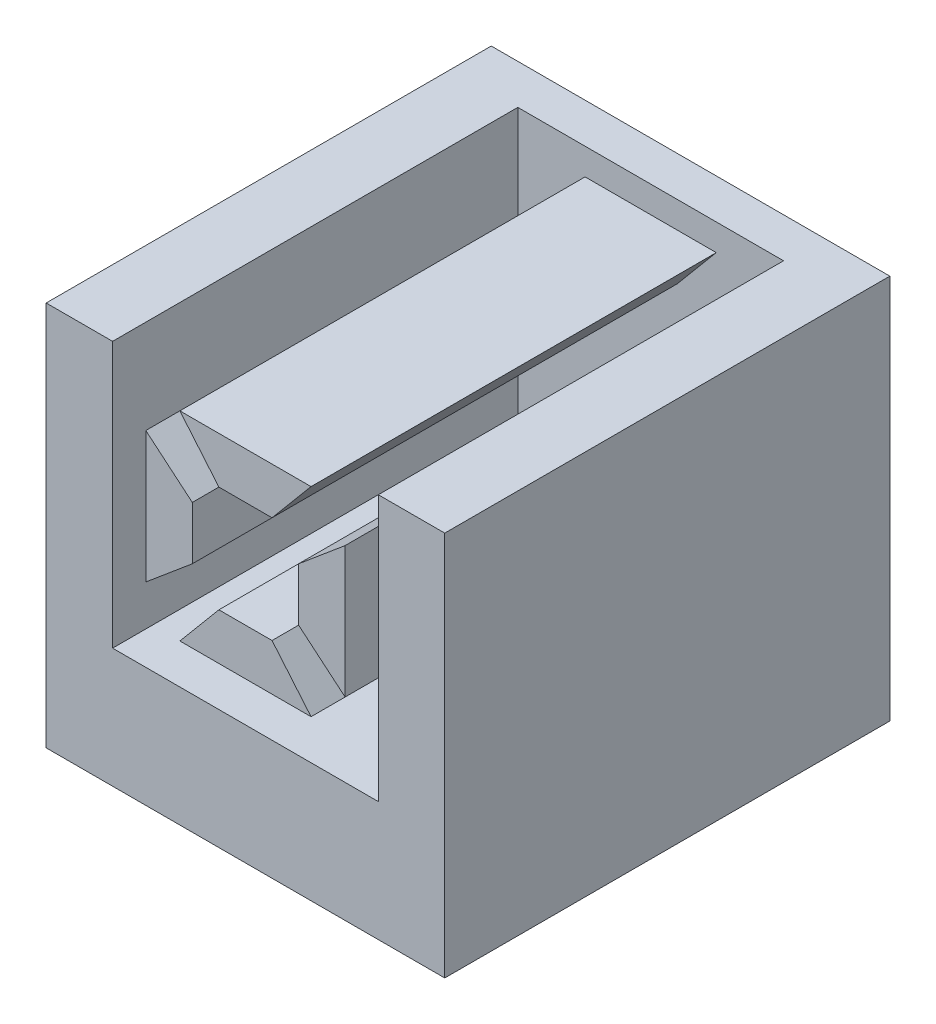
SolidWorks part; units mm, degrees
ref_plane "Front Plane" through (0, 0, 0) normal (0, 0, 1) x (1, 0, 0)
ref_plane "Top Plane" through (0, 0, 0) normal (0, 1, 0) x (1, 0, 0)
ref_plane "Right Plane" through (0, 0, 0) normal (1, 0, 0) x (0, 0, -1)
sketch "Sketch1" plane through (0, 0, 0) normal (0, 1, 0) x (1, 0, 0)
  line L0 (27.5, 55) -> (27.5, 0) construction
  line L1 (5, 0) -> (50, 0)
  line L2 (0, 5) -> (0, 50)
  line L3 (5, 55) -> (50, 55)
  line L4 (55, 5) -> (55, 50)
  line L5 (0, 55) -> (7.5, 55) construction
  line L6 (0, 55) -> (0, 47.5) construction
  line L7 (0, 47.5) -> (7.5, 47.5) construction
  line L8 (7.5, 55) -> (7.5, 47.5) construction
  line L9 (0, 27.5) -> (55, 27.5) construction
  circle A0 centre (7.5, 47.5) radius 2.5
  circle A1 centre (47.5, 47.5) radius 2.5
  circle A2 centre (47.5, 7.5) radius 2.5
  circle A3 centre (7.5, 7.5) radius 2.5
  arc A4 (50, 0) -> (55, 5) centre (50, 5) ccw
  arc A5 (50, 55) -> (55, 50) centre (50, 50) cw
  arc A6 (0, 50) -> (5, 55) centre (5, 50) cw
  arc A7 (5, 0) -> (0, 5) centre (5, 5) cw
  point P23 (55, 55)
  point P29 (0, 0)
  dimension "D3" = 2
  dimension "D5" = 5
  dimension "D1" = 55
  dimension "D2" = 55
  dimension "D4" = 2
extrude "Boss-Extrude2" add sketch "Sketch1" along normal blind 8 and the other way blind 1
sketch "Sketch2" plane through (0, 8, 0) normal (0, 1, 0) x (1, 0, 0)
  line L0 (0, 27.5) -> (55, 27.5)
  line L1 (0, 50) -> (0, 5) construction
  line L2 (55, 5) -> (55, 50) construction
  line L4 (0, 27.5) -> (55, 27.5)
  line L5 (0, 27.5) -> (0, 55)
  line L6 (0, 55) -> (55, 55)
  line L7 (55, 27.5) -> (55, 55)
  circle M3 centre (7.5, 47.5) radius 2.5
  line M5 (55, 5) -> (55, 50)
  arc M6 (55, 50) -> (50, 55) centre (50, 50) ccw
  line M7 (50, 55) -> (5, 55)
  arc M8 (5, 55) -> (0, 50) centre (5, 50) ccw
  line M9 (0, 50) -> (0, 5)
  circle M12 centre (47.5, 47.5) radius 2.5
  dimension "D1" = 27.5
extrude "Cut-Extrude1" cut sketch "Sketch2" against normal through all both and the other way through all contours L0 M9 M5 M6 M7 M8 M12 M3
sketch "Sketch3" plane through (0, 0, -27.5) normal (0, 0, -1) x (-1, 0, 0)
  line L0 (0, -1) -> (0, 8) construction
  line L1 (-55, -1) -> (-37.5, -1) construction
  line L2 (-55, -1) -> (-55, 3.5) construction
  line L3 (-55, 3.5) -> (-37.5, 3.5) construction
  line L4 (-37.5, -1) -> (-37.5, 3.5) construction
  line L5 (0, -1) -> (-55, -1) construction
  circle A0 centre (-37.5, 3.5) radius 3.25
  circle A1 centre (-17.5, 3.5) radius 3.25
  point P10 (0, 3.5)
  dimension "D3" = 6.5
  dimension "D4" = 2
  dimension "D5" = 17.5
  dimension "D1" = 4.5
  dimension "D2" = 17.5
  dimension "D6" = 4.5
sketch3d "3DSketch1"
  point P0 (9.6264, 4.1069, -27.5)
sketch "Sketch5" plane through (0, 8, 0) normal (0, 1, 0) x (1, 0, 0)
  line L0 (27.5, 27.5) -> (27.5, 0)
  line L1 (0, 27.5) -> (55, 27.5) construction
  line L2 (5, 0) -> (50, 0) construction
  line L3 (27.5, 27.5) -> (27.5, 24)
  line L5 (27.5, 24) -> (23, 24)
  line L6 (27.5, 24) -> (27.5, 17.5)
  line L7 (27.5, 17.5) -> (23, 17.5)
  line L8 (23, 24) -> (23, 17.5)
  line L9 (27.5, 24) -> (32, 24)
  line L10 (27.5, 24) -> (27.5, 17.5)
  line L11 (27.5, 17.5) -> (32, 17.5)
  line L12 (32, 24) -> (32, 17.5)
  dimension "D1" = 3.5
  dimension "D2" = 6.5
  dimension "D3" = 4.5
  dimension "D4" = 4.5
  dimension "D5" = 6.5
extrude "Cut-Extrude5" cut sketch "Sketch3" against normal blind 15 draft 0.057 contours A0 | A1
extrude "Boss-Extrude3" add sketch "Sketch5" along normal blind 14.5 contours L5 L8 L7 L0 | L12 L9 L0 L11
sketch "Sketch6" plane through (0, 0, -24) normal (0, 0, -1) x (-1, 0, 0)
  line L0 (-27.5, 8) -> (-27.5, 17)
  line L1 (-32, 8) -> (-23, 8) construction
  circle A0 centre (-27.5, 17) radius 4
  dimension "D2" = 8
  dimension "D1" = 9
extrude "Cut-Extrude4" cut sketch "Sketch6" against normal blind 1.5
sketch "Sketch11" plane through (0, 0, -24) normal (0, 0, -1) x (-1, 0, 0)
  line L0 (-27.5, 22.5) -> (-25.5, 22.5)
  line L1 (-32.4368, 26) -> (-22.5632, 26)
  line L2 (-32, 22.5) -> (-23, 22.5) construction
  line L3 (-25.5, 22.5) -> (-27.5, 22.5)
  line L4 (-25.5, 22.5) -> (-29.5, 22.5)
  line L5 (-25.5, 22.5) -> (-25.5, 26)
  line L6 (-25.5, 26) -> (-29.5, 26)
  line L7 (-29.5, 22.5) -> (-29.5, 26)
  line L8 (-22.5632, 26) -> (-25.5, 22.5)
  line L9 (-29.5, 22.5) -> (-32.4368, 26)
  point P10 (-27.5, 26)
  line M9 (-23, 22.5) -> (-32, 22.5)
  dimension "D1" = 2
  dimension "D2" = 4
  dimension "D3" = 3.5
  dimension "D4" = 40
sketch "Sketch12" plane through (0, 8, 0) normal (0, 1, 0) x (1, 0, 0)
  line L0 (27.5, 17.5) -> (27.5, 0)
  line L1 (32, 17.5) -> (23, 17.5) construction
  line L2 (5, 0) -> (50, 0) construction
  line L3 (17, 0) -> (17, -30)
  line L4 (17, 0) -> (38, 0)
  line L5 (27.5, 0) -> (27.5, -30)
  line L6 (17, -30) -> (38, -30)
  line L7 (38, 0) -> (38, -30)
  point P9 (23.9675, 0)
  line M9 (5, 0) -> (50, 0)
  dimension "D1" = 30
  dimension "D2" = 10.5
extrude "Boss-Extrude7" add sketch "Sketch12" against normal blind 9 contours L7 L5 L6 M9 | L3 L6 L5 M9
sketch "Sketch15" plane through (0, 22.5, 0) normal (0, 1, 0) x (1, 0, 0)
  line L0 (32, 24) -> (32, 17.5) construction
  line L1 (32, 17.5) -> (23, 17.5)
  line L2 (32, 17.5) -> (32, 24)
  line L3 (32, 24) -> (23, 24)
  line L4 (23, 17.5) -> (23, 24)
  line L5 (32, 17.5) -> (23, 17.5) construction
extrude "Boss-Extrude8" add sketch "Sketch15" along normal blind 3.5
extrude "Boss-Extrude9" add sketch "Sketch11" against normal blind 54 contours L9 L7 L1 | L7 L5 L1 M9 | L8 L1 L5
fillet "Fillet4" radius 5 1 edges at (27.5, -1, 30)
sketch "Sketch18" plane through (0, 26, 0) normal (0, 1, 0) x (1, 0, 0)
  line L0 (32.4368, -30) -> (32.4368, 24) construction
  line L1 (22.5632, 24) -> (32.4368, 24)
  line L2 (22.5632, 24) -> (22.5632, 17.5)
  line L3 (22.5632, 17.5) -> (32.4368, 17.5)
  line L4 (32.4368, 24) -> (32.4368, 17.5)
  dimension "D1" = 6.5
extrude "Boss-Extrude11" add sketch "Sketch18" along normal blind 0.5
sketch "Sketch20" plane through (0, 8, 0) normal (0, 1, 0) x (1, 0, 0)
  line L0 (27.5, -1030) -> (27.5, 48970) construction
  line L1 (17, -30) -> (38, -30) construction
  line L2 (32, 17.5) -> (23, 17.5) construction
  line L3 (27.5, 17.5) -> (16.5, 17.5)
  line L4 (27.5, 17.5) -> (27.5, 0)
  line L5 (27.5, 0) -> (16.5, 0)
  line L6 (16.5, 17.5) -> (16.5, 0)
  line L7 (27.5, 17.5) -> (16.5, 0) construction
  line L8 (27.5, 0) -> (16.5, 17.5) construction
  line L10 (27.5, 17.5) -> (38.5, 17.5)
  line L11 (27.5, 17.5) -> (27.5, 0)
  line L12 (27.5, 0) -> (38.5, 0)
  line L13 (38.5, 17.5) -> (38.5, 0)
  line L14 (27.5, 17.5) -> (38.5, 0) construction
  line L15 (27.5, 0) -> (38.5, 17.5) construction
  line L16 (38.5, 17.5) -> (42.5, 17.5)
  line L17 (38.5, 17.5) -> (38.5, 0)
  line L18 (38.5, 0) -> (42.5, 0)
  line L19 (42.5, 17.5) -> (42.5, 0)
  line L21 (16.5, 17.5) -> (12.5, 17.5)
  line L22 (16.5, 17.5) -> (16.5, 0)
  line L23 (16.5, 0) -> (12.5, 0)
  line L24 (12.5, 17.5) -> (12.5, 0)
  line L26 (42.5, 0) -> (38.5, 0)
  line L27 (42.5, 0) -> (42.5, 17.5)
  line L28 (42.5, 17.5) -> (38.5, 17.5)
  line L29 (38.5, 0) -> (38.5, 17.5)
  line L30 (16.5, 0) -> (12.5, 0)
  line L31 (16.5, 0) -> (16.5, 17.5)
  line L32 (16.5, 17.5) -> (12.5, 17.5)
  line L33 (12.5, 0) -> (12.5, 17.5)
  point P5 (27.5, -30)
  point P9 (22, 8.75)
  point P14 (33, 8.75)
  line M12 (5, 0) -> (17, 0)
  line M16 (38, 0) -> (50, 0)
  dimension "D2" = 11
  dimension "D3" = 17.5
  dimension "D4" = 4
extrude "Boss-Extrude12" add sketch "Sketch20" along normal blind 18 contours L21 L24 L6 M12 | L19 L16 L13 M16
sketch "Sketch21" plane through (12.5, 0, 0) normal (-1, 0, 0) x (0, 0, 1)
  line L0 (-17.5, 26) -> (-17.5, 8) construction
  line L1 (0, 26) -> (-17.5, 26)
  line L2 (0, 26) -> (0, 24)
  line L3 (0, 24) -> (-17.5, 24)
  line L4 (-17.5, 26) -> (-17.5, 24)
  dimension "D1" = 2
sketch "Sketch22" plane through (12.5, 0, 0) normal (-1, 0, 0) x (0, 0, 1)
  line L1 (-17.5, 24) -> (0, 24)
  line L2 (-17.5, 24) -> (-17.5, 28)
  line L3 (-17.5, 28) -> (0, 28)
  line L4 (0, 24) -> (0, 28)
  dimension "D1" = 4
extrude "Boss-Extrude13" add sketch "Sketch22" along normal blind 11 and the other way blind 4 contours L3 L4 L1 L2
sketch "Sketch25" plane through (0, 28, 0) normal (0, 1, 0) x (1, 0, 0)
  line L2 (1.5, 17.5) -> (16.5, 17.5) construction
  line L3 (1.5, 0) -> (3.5, 0)
  line L4 (1.5, 0) -> (1.5, 17.5)
  line L5 (1.5, 17.5) -> (3.5, 17.5)
  line L6 (3.5, 0) -> (3.5, 17.5)
  dimension "D1" = 2
extrude "Boss-Extrude14" add sketch "Sketch25" along normal blind 41
sketch "Sketch28" plane through (1.5, 0, 0) normal (-1, 0, 0) x (0, 0, 1)
  line L2 (0, 69) -> (-41, 69)
  line L3 (0, 69) -> (0, 24)
  line L4 (0, 24) -> (-41, 24)
  line L5 (-41, 69) -> (-41, 24)
  dimension "D1" = 45
  dimension "D2" = 41
extrude "Boss-Extrude15" add sketch "Sketch28" against normal blind 2
sketch "Sketch29" plane through (1.5, 0, 0) normal (-1, 0, 0) x (0, 0, 1)
  line L1 (0, 24) -> (-5, 24)
  line L2 (0, 24) -> (0, 33)
  line L3 (0, 33) -> (-5, 33)
  line L4 (-5, 24) -> (-5, 33)
  circle A0 centre (-5, 33) radius 1.75
  circle A1 centre (-36, 33) radius 1.75
  circle A2 centre (-36, 64) radius 1.75
  circle A3 centre (-5, 64) radius 1.75
  dimension "D3" = 3.5
  dimension "D6" = 31
  dimension "D1" = 9
  dimension "D2" = 5
  dimension "D7" = 31
  dimension "D4" = 2
  dimension "D5" = 2
extrude "Cut-Extrude8" cut sketch "Sketch29" against normal blind 9 contours A1 | A3 | A0 | A2
sketch "Sketch30" plane through (42.5, 0, 0) normal (1, 0, 0) x (0, 0, -1)
  line L0 (17.5, 26) -> (17.5, 8) construction
  line L1 (0, 26) -> (17.5, 26)
  line L2 (0, 26) -> (0, 24)
  line L3 (0, 24) -> (17.5, 24)
  line L4 (17.5, 26) -> (17.5, 24)
  line L6 (0, 24) -> (17.5, 24)
  line L7 (0, 24) -> (0, 28)
  line L8 (0, 28) -> (17.5, 28)
  line L9 (17.5, 24) -> (17.5, 28)
  line M4 (17.5, 8) -> (17.5, 26)
  line M5 (17.5, 26) -> (0, 26)
  line M6 (0, 26) -> (0, 8)
  dimension "D1" = 2
  dimension "D2" = 4
extrude "Boss-Extrude16" add sketch "Sketch30" along normal blind 9 and the other way blind 4 contours L3 M6 M4 M5 | L9 L8 L7 M5
sketch "Sketch31" plane through (3.5, 0, 0) normal (1, 0, 0) x (0, 0, -1)
  line L1 (41, 69) -> (20.5, 69)
  line L2 (41, 69) -> (41, 47)
  line L3 (41, 47) -> (20.5, 47)
  line L4 (20.5, 69) -> (20.5, 47)
  circle A0 centre (20.5, 47) radius 10
  dimension "D3" = 20
  dimension "D1" = 22
  dimension "D2" = 20.5
extrude "Cut-Extrude9" cut sketch "Sketch31" against normal blind 9 contours L4 A0 L3 | L3 A0 L4
sketch "Sketch32" plane through (0, 0, -17.5) normal (0, 0, -1) x (-1, 0, 0)
  line L1 (-16.5, 28) -> (-3.5, 28)
  line L2 (-16.5, 28) -> (-16.5, 24)
  line L3 (-16.5, 24) -> (-3.5, 24)
  line L4 (-3.5, 28) -> (-3.5, 24)
extrude "Boss-Extrude17" add sketch "Sketch32" along normal blind 23.5
sketch "Sketch33" plane through (0, 8, 0) normal (0, 1, 0) x (1, 0, 0)
  line L0 (38.5, 17.5) -> (38.5, 0)
  line L1 (38.5, 17.5) -> (38, 17.5)
  line L2 (38.5, 0) -> (38, 0)
  line L3 (38, 17.5) -> (38, 0)
  line L4 (16.5, 17.5) -> (16.5, 0)
  line L5 (16.5, 17.5) -> (17, 17.5)
  line L6 (16.5, 0) -> (17, 0)
  line L7 (17, 17.5) -> (17, 0)
  dimension "D1" = 0.5
  dimension "D2" = 0.5
extrude "Boss-Extrude18" add sketch "Sketch33" along normal blind 20
sketch "Sketch34" plane through (0, 0, 0) normal (0, 0, 1) x (1, 0, 0)
  line L0 (42.5, 24) -> (42.5, 8) construction
  line L1 (51.5, 28) -> (42.5, 28)
  line L2 (51.5, 28) -> (51.5, 24)
  line L3 (51.5, 24) -> (42.5, 24)
  line L4 (42.5, 28) -> (42.5, 24)
  line L5 (42.5, 24) -> (51.5, 24) construction
  line L7 (42.5, 28) -> (38, 28)
  line L8 (42.5, 28) -> (42.5, -1)
  line L9 (42.5, -1) -> (38, -1)
  line L10 (38, 28) -> (38, -1)
  line L11 (17, 28) -> (1.5, 28)
  line L12 (17, 28) -> (17, 24)
  line L13 (17, 24) -> (1.5, 24)
  line L14 (1.5, 28) -> (1.5, 24)
  line L15 (12.5, 24) -> (17, 24)
  line L16 (12.5, 24) -> (12.5, -1)
  line L17 (12.5, -1) -> (17, -1)
  line L18 (17, 24) -> (17, -1)
  line M1 (42.5, 8) -> (42.5, 24)
  line M2 (42.5, 24) -> (51.5, 24)
  line M3 (51.5, 24) -> (51.5, 28)
  line M4 (51.5, 28) -> (38, 28)
  line M5 (38, 28) -> (38, 8)
  line M6 (38, 8) -> (38, -1)
  line M7 (38, -1) -> (50, -1)
extrude "Boss-Extrude19" add sketch "Sketch34" along normal blind 26 contours L18 L13 L16 L17 | L11 L14 L13 L12 | L8 L4 M1 M4 M5 M6 M7 | L4 M4 M2 M3
sketch "Sketch35" plane through (0, 0, -17.5) normal (0, 0, 1) x (1, 0, 0)
  line L1 (32.4368, 26.5) -> (22.5632, 26.5)
  line L2 (32.4368, 26.5) -> (32.4368, 26)
  line L3 (32.4368, 26) -> (22.5632, 26)
  line L4 (22.5632, 26.5) -> (22.5632, 26)
extrude "Boss-Extrude20" add sketch "Sketch35" along normal blind 47.5
sketch "Sketch37" plane through (0, 0, -17.5) normal (0, 0, 1) x (1, 0, 0)
  line L0 (27.5, 8) -> (29.5, 8)
  line L2 (32, 8) -> (23, 8) construction
  line L3 (29.5, 12) -> (33.1362, 7.6666)
  line L4 (29.5, 8) -> (25.5, 8)
  line L5 (29.5, 8) -> (29.5, 12)
  line L6 (29.5, 12) -> (25.5, 12)
  line L7 (25.5, 8) -> (25.5, 12)
  line L8 (25.5, 12) -> (21.8638, 7.6666)
  line L9 (21.8638, 7.6666) -> (33.1362, 7.6666)
  line M8 (32, 8) -> (32, 25.4794)
  line M12 (23, 25.4794) -> (23, 8)
  line M13 (23, 8) -> (32, 8)
  dimension "D1" = 2
  dimension "D2" = 4
  dimension "D3" = 4
  dimension "D4" = 40
  dimension "D5" = 40
extrude "Boss-Extrude21" add sketch "Sketch37" along normal blind 47.5 contours L7 L8 M12 M13 | L7 L5 L6 M13 | L5 L3 M13 M8 | L8 L9 L3 M8 M13 M12
sketch "Sketch38" plane through (0, 0, 30) normal (0, 0, 1) x (1, 0, 0)
  line L1 (22.5632, 26.5) -> (22.1436, 26.5)
  line L2 (22.5632, 26.5) -> (22.5632, 8)
  line L3 (22.5632, 8) -> (22.1436, 8)
  line L4 (22.1436, 26.5) -> (22.1436, 8)
  line L5 (32.4368, 26.5) -> (32.8564, 26.5)
  line L6 (32.4368, 26.5) -> (32.4368, 8)
  line L7 (32.4368, 8) -> (32.8564, 8)
  line L8 (32.8564, 26.5) -> (32.8564, 8)
extrude "Cut-Extrude10" cut sketch "Sketch38" against normal blind 90.5
sketch "Sketch39" plane through (0, 0, 30) normal (0, 0, 1) x (1, 0, 0)
  line L0 (27.784, 26.1035) -> (27.5, 26.5)
  line L1 (32.4368, 26.5) -> (38, 26.5)
  line L2 (32.4368, 26.5) -> (32.4368, 8)
  line L3 (32.4368, 8) -> (38, 8)
  line L4 (38, 26.5) -> (38, 8)
  line L5 (32.4368, 26.5) -> (22.5632, 26.5) construction
  line L6 (27.5, 26.5) -> (27.5, 8)
  line L7 (38, 17.25) -> (38, 19.25)
  line L8 (34, 19.25) -> (38, 22.6064)
  line L9 (38, 19.25) -> (34, 19.25)
  line L10 (38, 19.25) -> (38, 15.25)
  line L11 (38, 15.25) -> (34, 15.25)
  line L12 (34, 19.25) -> (34, 15.25)
  line L13 (34, 15.25) -> (38, 11.8936)
  line L14 (22.5632, 8.5) -> (21.9673, 8)
  line L15 (17, 8) -> (22.5632, 8) construction
  line L16 (17, 22.6064) -> (17.7151, 22.6064)
  line L17 (38, 22.6064) -> (37.2849, 22.6064)
  line L18 (38, 22.6064) -> (38, 22.0064)
  line L19 (38, 22.0064) -> (37.2849, 22.0064)
  line L20 (37.2849, 22.6064) -> (37.2849, 22.0064)
  line L21 (38, 11.8936) -> (37.2849, 11.8936)
  line L22 (38, 11.8936) -> (38, 12.4936)
  line L23 (38, 12.4936) -> (37.2849, 12.4936)
  line L24 (37.2849, 11.8936) -> (37.2849, 12.4936)
  line L25 (17.7151, 22.6064) -> (17.7151, 22.0064)
  line L26 (17, 22.0064) -> (17.7151, 22.0064)
  line L27 (21, 19.25) -> (17, 22.6064)
  line L28 (21, 19.25) -> (21, 15.25)
  line L29 (17, 19.25) -> (21, 19.25)
  line L30 (17.7151, 11.8936) -> (17.7151, 12.4936)
  line L31 (17, 11.8936) -> (17.7151, 11.8936)
  line L32 (17, 12.4936) -> (17.7151, 12.4936)
  line L33 (17, 26.5) -> (17, 8)
  line L34 (17, 15.25) -> (21, 15.25)
  line L35 (21, 15.25) -> (17, 11.8936)
  line L36 (17, 19.25) -> (17, 22.0064)
  line L37 (17, 22.0064) -> (17.7151, 22.0064)
  line L38 (17.7151, 22.0064) -> (21, 19.25)
  line L39 (17, 19.25) -> (21, 19.25)
  dimension "D1" = 2
  dimension "D2" = 4
  dimension "D3" = 4
  dimension "D4" = 40
  dimension "D5" = 40
  dimension "D6" = 0.6
  dimension "D7" = 0.6
extrude "Boss-Extrude23" add sketch "Sketch39" against normal blind 47.5 contours L26 L33 L29 L27 | L33 L34 L28 L29 | L35 L34 L33 L32 | L23 L4 L11 L13 | L9 L12 L11 L4 | L4 L19 L8 L9
ref_plane "Plane1" through (5, 8, 0) normal (0, 1, 0) x (1, 0, 0)
sketch "Sketch45" plane through (0, 8, 0) normal (0, 1, 0) x (1, 0, 0)
  line L0 (0, 15.4413) -> (0, -89.262) construction
  line L1 (-11, 15.4413) -> (-11, -89.262)
  dimension "D1" = 11
sketch "Sketch46" plane through (0, 0, 0) normal (-1, 0, 0) x (0, 0, 1)
  line L1 (-27.5, -1) -> (-5, -1)
  line L2 (-27.5, -1) -> (-27.5, 8)
  line L3 (-27.5, 8) -> (-5, 8)
  line L4 (-5, -1) -> (-5, 8)
  line L5 (-27.5, 8) -> (0, 8)
  line L6 (-27.5, 8) -> (-27.5, -1)
  line L7 (-27.5, -1) -> (0, -1)
  line L8 (0, 8) -> (0, -1)
  line M2 (-27.5, 8) -> (-27.5, -1)
  line M3 (-27.5, -1) -> (-5, -1)
  line M4 (-5, -1) -> (-5, 8)
  line M5 (-5, 8) -> (-27.5, 8)
  dimension "D1" = 27.5
extrude "Boss-Extrude26" add sketch "Sketch46" against normal blind 11.5 contours M5 M2 M3 M4 | L8 L5 L7 M4
sketch "Sketch47" plane through (0, 0, 0) normal (-1, 0, 0) x (0, 0, 1)
  line L1 (-27.5, 8) -> (0, 8)
  line L2 (-27.5, 8) -> (-27.5, -1)
  line L3 (-27.5, -1) -> (0, -1)
  line L4 (0, 8) -> (0, -1)
extrude "Boss-Extrude27" add sketch "Sketch47" along normal blind 11
sketch "Sketch48" plane through (0, 8, 0) normal (0, 1, 0) x (1, 0, 0)
  line L0 (12.5, 17.5) -> (12.5, 24)
  line L1 (23, 24) -> (12.5, 24)
  line L2 (23, 24) -> (23, 17.5)
  line L3 (23, 17.5) -> (12.5, 17.5)
  line L4 (12.5, 24) -> (12.5, 17.5)
  line L5 (12.5, 17.5) -> (7.5, 17.5)
  line L6 (12.5, 24) -> (7.5, 24)
  line L7 (7.5, 17.5) -> (7.5, 24)
  line L8 (42.5, 24) -> (42.5, 17.5)
  line L9 (32, 24) -> (42.5, 24)
  line L10 (32, 24) -> (32, 17.5)
  line L11 (32, 17.5) -> (42.5, 17.5)
  line L12 (42.5, 24) -> (42.5, 17.5)
  line L13 (42.5, 24) -> (47.5, 24)
  line L14 (42.5, 17.5) -> (47.5, 17.5)
  line L15 (47.5, 24) -> (47.5, 17.5)
  line M3 (12.5, 17.5) -> (17, 17.5)
  line M8 (22.5632, 17.5) -> (23, 17.5)
  line M9 (23, 17.5) -> (23, 24)
  line M11 (32, 24) -> (32, 17.5)
  line M12 (32, 17.5) -> (32.4368, 17.5)
  line M17 (38, 17.5) -> (42.5, 17.5)
  dimension "D1" = 5
  dimension "D2" = 5
sketch "Sketch49" plane through (0, 0, -24) normal (0, 0, -1) x (-1, 0, 0)
  line L0 (-17.5, 3.5) -> (-27.5, 17)
  line L1 (-27.5, 17) -> (-17.5, 17)
  line L2 (-17.5, 17) -> (-17.5, 3.5)
  line L3 (-27.5, 17) -> (-37.5, 3.5)
  line L4 (-37.5, 3.5) -> (-37.5, 17)
  line L5 (-37.5, 17) -> (-27.5, 17)
  circle A0 centre (-37.5, 17) radius 4
  circle A1 centre (-17.5, 17) radius 4
  dimension "D1" = 8
  dimension "D2" = 8
extrude "Boss-Extrude31" add sketch "Sketch48" along normal blind 18.5 contours L11 L8 L9 M12 M17 M11 | L15 L13 L8 L14 | L3 L1 L0 M8 M9 M3 | L7 L5 L0 L6
sketch "Sketch50" plane through (0, 0, -24) normal (0, 0, -1) x (-1, 0, 0)
  circle A0 centre (-17.5, 17) radius 4
  circle A1 centre (-37.5, 17) radius 4
  dimension "D1" = 8
  dimension "D2" = 8
extrude "Cut-Extrude11" cut sketch "Sketch50" against normal blind 1.5
sketch "Sketch51" plane through (0, 0, -24) normal (0, 0, -1) x (-1, 0, 0)
  line L1 (-32.4593, 12.5515) -> (-22.8331, 12.5515)
  line L2 (-32.4593, 12.5515) -> (-32.4593, 21.6767)
  line L3 (-32.4593, 21.6767) -> (-22.8331, 21.6767)
  line L4 (-22.8331, 12.5515) -> (-22.8331, 21.6767)
extrude "Boss-Extrude32" add sketch "Sketch51" against normal blind 1.5
sketch "Sketch53" plane through (0, 0, -24) normal (0, 0, -1) x (-1, 0, 0)
  line L0 (-27.5, 17) -> (-27.5, 8)
  line L1 (-47.5, 8) -> (-7.5, 8) construction
  line L2 (-27.5, 8) -> (-27.5, 26.5)
  line L3 (-47.5, 26.5) -> (-16.5, 26.5) construction
  line L4 (-27.5, 17.25) -> (-23.5, 17.25)
  line L5 (-23.5, 17.25) -> (-31.5, 17.25)
  line L7 (-31.5, 13.25) -> (-23.5, 13.25)
  line L8 (-31.5, 13.25) -> (-31.5, 21.25)
  line L9 (-31.5, 21.25) -> (-23.5, 21.25)
  line L10 (-23.5, 13.25) -> (-23.5, 21.25)
  line L11 (-31.5, 13.25) -> (-23.5, 21.25) construction
  line L12 (-31.5, 21.25) -> (-23.5, 13.25) construction
  dimension "D1" = 4
  dimension "D2" = 4
  dimension "D3" = 8
  dimension "D4" = 8
sketch "Sketch54" plane through (0, 0, -17.5) normal (0, 0, 1) x (1, 0, 0)
  line L0 (27.5, 22.5) -> (27.5, 14.5)
  line L1 (29.5, 22.5) -> (25.5, 22.5) construction
  line L3 (23.5, 22.5) -> (31.5, 22.5)
  line L4 (23.5, 22.5) -> (23.5, 14.5)
  line L5 (23.5, 14.5) -> (31.5, 14.5)
  line L6 (31.5, 22.5) -> (31.5, 14.5)
  line L7 (23.5, 22.5) -> (31.5, 14.5) construction
  line L8 (23.5, 14.5) -> (31.5, 22.5) construction
  point P4 (27.5, 18.5)
  line M17 (29.5, 22.5) -> (25.5, 22.5)
  dimension "D1" = 8
  dimension "D2" = 8
  dimension "D3" = 8
extrude "Boss-Extrude35" add sketch "Sketch54" along normal blind 47.5 contours L6 L3 L0 L5 M17 | L4 L5 L0 L3 M17
sketch "Sketch55" plane through (0, 0, 30) normal (0, 0, 1) x (1, 0, 0)
  line L1 (32.4368, 26.5) -> (22.5632, 26.5)
  line L2 (32.4368, 26.5) -> (32.4368, 26)
  line L3 (32.4368, 26) -> (22.5632, 26)
  line L4 (22.5632, 26.5) -> (22.5632, 26)
extrude "Cut-Extrude12" cut sketch "Sketch55" against normal blind 47.5
sketch "Sketch56" plane through (0, 0, 26) normal (0, 0, 1) x (1, 0, 0)
  line L1 (38, 28) -> (37.5, 28)
  line L2 (38, 28) -> (38, 8)
  line L3 (38, 8) -> (37.5, 8)
  line L4 (37.5, 28) -> (37.5, 8)
  line L5 (17, 28) -> (17.5, 28)
  line L6 (17, 28) -> (17, 8)
  line L7 (17, 8) -> (17.5, 8)
  line L8 (17.5, 28) -> (17.5, 8)
  dimension "D1" = 0.5
  dimension "D2" = 0.5
extrude "Boss-Extrude36" add sketch "Sketch56" against normal blind 43.5
sketch "Sketch57" plane through (0, 0, 30) normal (0, 0, 1) x (1, 0, 0)
  line L0 (31.5, 20.5) -> (31.5, 16.5)
  line L1 (35, 18.4644) -> (35, 13.5632)
  line L2 (25.5, 22.5) -> (29.5, 22.5)
  line L3 (29.5, 22.5) -> (32.4368, 26)
  line L4 (29.5, 22.5) -> (29.5, 26)
  line L5 (22.5632, 26) -> (32.4368, 26) construction
  line L6 (31.5, 22.5) -> (31.5, 14.5) construction
  line L7 (35, 13.5632) -> (31.5, 16.5)
  line L8 (31.5, 16.5) -> (35, 16.5)
  line L9 (31.5, 16.5) -> (31.5, 20.4288)
  line L10 (31.5, 20.4288) -> (35, 20.4288)
  line L11 (35, 16.5) -> (35, 20.4288)
  line L12 (35, 18.5356) -> (35, 23.4368)
  line L13 (35, 16.5) -> (31.5, 16.5)
  line L14 (35, 16.5) -> (35, 18.5)
  line L15 (35, 18.5) -> (31.5, 18.5)
  line L16 (31.5, 16.5) -> (31.5, 18.5)
  line L17 (35, 23.4368) -> (31.5, 20.5)
  line L18 (27.5, 22.5) -> (27.5, 14.5) construction
  line L19 (23.5, 14.5) -> (31.5, 14.5) construction
  line L20 (20, 13.5632) -> (23.5, 16.5)
  line L21 (23.5, 16.5) -> (20, 16.5)
  line L22 (20, 18.4644) -> (20, 13.5632)
  line L23 (20, 18.5356) -> (20, 23.4368)
  line L24 (20, 23.4368) -> (23.5, 20.5)
  line L25 (23.5, 20.5) -> (23.5, 16.5)
  line L26 (27.5, 18.5) -> (31.5, 18.5) construction
  line L27 (31.5, 18.5) -> (23.5, 18.5) construction
  line L28 (23.5, 20.5) -> (23.5, 16.5)
  line L29 (32.4368, 26) -> (22.5632, 26)
  line L30 (22.5632, 26) -> (25.5, 22.5)
  line L31 (25.5, 14.5) -> (29.5, 14.5)
  line L32 (22.5632, 11) -> (25.5, 14.5)
  line L33 (32.4368, 11) -> (22.5632, 11)
  line L34 (29.5, 14.5) -> (32.4368, 11)
  line L35 (23.5, 16.5) -> (20, 13.5632)
  line L36 (20, 13.5632) -> (20, 23.4368)
  line L37 (20, 23.4368) -> (23.5, 20.5)
  line L38 (23.5, 18.5) -> (23.5, 20.5)
  line M12 (23.5, 22.5) -> (23.5, 14.5)
  line M13 (23.5, 14.5) -> (31.5, 14.5)
  line M14 (31.5, 14.5) -> (31.5, 22.5)
  dimension "D1" = 2
  dimension "D2" = 3.5
  dimension "D3" = 130
extrude "Boss-Extrude37" add sketch "Sketch57" against normal blind 47.5 contours L12 L17 L0 L10 | L15 L11 L10 L9 | L11 L15 L8 L1 M14 | L8 L7 L1 | L34 L32 L33 M13 | L36 L22 L21 L28 L24 L23 M12 | L21 L22 L20
sketch "Sketch58" plane through (0, 0, 30) normal (0, 0, 1) x (1, 0, 0)
  line L1 (38, 22.0064) -> (37.2849, 22.0064)
  line L2 (38, 22.0064) -> (38, 12.4936)
  line L3 (38, 12.4936) -> (37.2849, 12.4936)
  line L4 (37.2849, 22.0064) -> (37.2849, 12.4936)
  line L5 (17, 22.0064) -> (17.7151, 22.0064)
  line L6 (17, 22.0064) -> (17, 12.4936)
  line L7 (17, 12.4936) -> (17.7151, 12.4936)
  line L8 (17.7151, 22.0064) -> (17.7151, 12.4936)
extrude "Cut-Extrude13" cut sketch "Sketch58" against normal blind 4
sketch "Sketch59" plane through (0, 0, 30) normal (0, 0, 1) x (1, 0, 0)
  line L0 (37.2849, 22.0064) -> (35, 20.0891)
  line L1 (35, 20.0891) -> (35, 14.4109)
  line L2 (35, 14.4109) -> (37.2849, 12.4936)
  line L3 (37.2849, 12.4936) -> (37.2849, 22.0064)
  line L4 (17.7151, 22.0064) -> (20, 20.0891)
  line L5 (20, 20.0891) -> (20, 14.4109)
  line L6 (20, 14.4109) -> (17.7151, 12.4936)
  line L7 (20, 14.4109) -> (17.7151, 12.4936) construction
  line L8 (17.7151, 12.4936) -> (17.7151, 22.0064)
extrude "Cut-Extrude15" cut sketch "Sketch59" against normal blind 47.5
sketch "Sketch60" plane through (0, 0, 26) normal (0, 0, 1) x (1, 0, 0)
  line L0 (17.7151, 12.4936) -> (17.7151, 22.0064) construction
  line L1 (37.2849, 22.0064) -> (37.5, 22.0064)
  line L2 (37.2849, 22.0064) -> (37.2849, 12.4936)
  line L3 (37.2849, 12.4936) -> (37.5, 12.4936)
  line L4 (37.5, 22.0064) -> (37.5, 12.4936)
  line L5 (17.5, 22.0064) -> (17.7151, 22.0064)
  line L6 (17.5, 22.0064) -> (17.5, 12.4936)
  line L7 (17.5, 12.4936) -> (17.7151, 12.4936)
  line L8 (17.7151, 22.0064) -> (17.7151, 12.4936)
extrude "Cut-Extrude16" cut sketch "Sketch60" against normal blind 47.5
sketch "Sketch61" plane through (0, 0, 30) normal (0, 0, 1) x (1, 0, 0)
  line L0 (32.4368, 8) -> (22.5632, 8)
  line L1 (22.5632, 8) -> (22.5632, 8.5)
  line L2 (22.5632, 8.5) -> (24.6609, 11)
  line L3 (24.6609, 11) -> (30.3391, 11)
  line L4 (30.3391, 11) -> (32.4368, 8.5)
  line L5 (32.4368, 8.5) -> (32.4368, 8)
extrude "Cut-Extrude17" cut sketch "Sketch61" against normal blind 47.5
sketch "Sketch62" plane through (0, 0, 30) normal (0, 0, 1) x (1, 0, 0)
  line L1 (23.5, 22.5) -> (31.5, 22.5)
  line L2 (23.5, 22.5) -> (23.5, 14.5)
  line L3 (23.5, 14.5) -> (31.5, 14.5)
  line L4 (31.5, 22.5) -> (31.5, 14.5)
extrude "Cut-Extrude18" cut sketch "Sketch62" against normal blind 47.5
sketch "Sketch63" plane through (0, 0, -41) normal (0, 0, -1) x (-1, 0, 0)
  line L1 (-3.5, 28) -> (-16.5, 28)
  line L2 (-3.5, 28) -> (-3.5, 24)
  line L3 (-3.5, 24) -> (-16.5, 24)
  line L4 (-16.5, 28) -> (-16.5, 24)
extrude "Cut-Extrude20" cut sketch "Sketch63" against normal blind 17
sketch "Sketch64" plane through (0, 0, -17.5) normal (0, 0, -1) x (-1, 0, 0)
  line L1 (-17.5, 26.5) -> (-16.5, 26.5)
  line L2 (-17.5, 26.5) -> (-17.5, 28)
  line L3 (-17.5, 28) -> (-16.5, 28)
  line L4 (-16.5, 26.5) -> (-16.5, 28)
extrude "Boss-Extrude38" add sketch "Sketch64" along normal blind 6.5
sketch "Sketch65" plane through (0, 28, 0) normal (0, 1, 0) x (1, 0, 0)
  line L1 (51.5, 17.5) -> (44.5, 17.5)
  line L2 (51.5, 17.5) -> (51.5, 14.5)
  line L3 (51.5, 14.5) -> (44.5, 14.5)
  line L4 (44.5, 17.5) -> (44.5, 14.5)
  dimension "D1" = 3
  dimension "D2" = 7
extrude "Cut-Extrude21" cut sketch "Sketch65" against normal blind 1.5
sketch "Sketch66" plane through (1.5, 0, 0) normal (-1, 0, 0) x (0, 0, 1)
  line L0 (-10.5, 47) -> (-30.5, 47)
  line L2 (-31.5643, 36.4388) -> (-9.4357, 36.4388)
  line L3 (-31.5643, 36.4388) -> (-31.5643, 57.5612)
  line L4 (-31.5643, 57.5612) -> (-9.4357, 57.5612)
  line L5 (-9.4357, 36.4388) -> (-9.4357, 57.5612)
  line L6 (-31.5643, 36.4388) -> (-9.4357, 57.5612) construction
  line L7 (-31.5643, 57.5612) -> (-9.4357, 36.4388) construction
  circle A0 centre (-20.5, 47) radius 10 construction
  point P5 (-20.5, 47)
  circle M1 centre (-20.5, 47) radius 10
extrude "Boss-Extrude39" add sketch "Sketch66" against normal blind 2 contours L0 M1 | L0 M1
sketch "Sketch67" plane through (1.5, 0, 0) normal (-1, 0, 0) x (0, 0, 1)
  line L0 (0, 28) -> (-41, 28)
  line L1 (-41, 69) -> (-41, 24) construction
  line L2 (-41, 28) -> (-20.5, 28)
  line L3 (-20.5, 28) -> (-20.5, 69)
  line L4 (-41, 69) -> (0, 69) construction
  line L5 (-20.5, 69) -> (-20.5, 48.5)
  line L6 (-20.5, 48.5) -> (-41, 48.5)
  line L7 (-41, 48.5) -> (0, 48.5)
  line L8 (0, 28) -> (0, 69) construction
  circle A0 centre (-20.5, 48.5) radius 12.5
  dimension "D1" = 25
extrude "Cut-Extrude22" cut sketch "Sketch67" against normal blind 155 contours L7 A0 L3 | L3 A0 L7 | L6 A0 L3 | L3 A0 L6
sketch "Sketch70" plane through (47.5, 0, 0) normal (1, 0, 0) x (0, 0, -1)
  line L1 (17.5, 8) -> (32.339, 8)
  line L2 (17.5, 8) -> (17.5, 35.5991)
  line L3 (17.5, 35.5991) -> (32.339, 35.5991)
  line L4 (32.339, 8) -> (32.339, 35.5991)
  line L5 (17.5, 8) -> (33.2739, 8)
  line L6 (17.5, 8) -> (17.5, -11.9538)
  line L7 (17.5, -11.9538) -> (33.2739, -11.9538)
  line L8 (33.2739, 8) -> (33.2739, -11.9538)
  line M1 (17.5, 8) -> (24, 8)
  line M2 (24, 8) -> (24, 26.5)
  line M3 (24, 26.5) -> (17.5, 26.5)
  line M4 (17.5, 26.5) -> (17.5, 24)
  line M5 (17.5, 24) -> (17.5, 8)
extrude "Cut-Extrude24" cut sketch "Sketch70" against normal through all and the other way through all contours L1 L4 L3 L2 M3 M2 | L8 L5 L1 L6 L7 M1 | M5 M1 M2 M3 M4
sketch "Sketch71" plane through (3.5, 0, 0) normal (1, 0, 0) x (0, 0, -1)
  line L1 (0, 28) -> (61.2895, 28)
  line L2 (0, 28) -> (0, 98.3292)
  line L3 (0, 98.3292) -> (61.2895, 98.3292)
  line L4 (61.2895, 28) -> (61.2895, 98.3292)
  line L5 (32.3693, 28) -> (79.9367, 28)
  line L6 (32.3693, 28) -> (32.3693, 8.1938)
  line L7 (32.3693, 8.1938) -> (79.9367, 8.1938)
  line L8 (79.9367, 28) -> (79.9367, 8.1938)
  circle M1 centre (36, 64) radius 1.75
  circle M2 centre (5, 33) radius 1.75
  circle M3 centre (5, 64) radius 1.75
  circle M4 centre (36, 33) radius 1.75
  circle M5 centre (20.5, 48.5) radius 12.5
  line M6 (17.5, 28) -> (17.5, 35.5991)
  line M7 (17.5, 35.5991) -> (32.339, 35.5991)
  line M8 (32.339, 35.5991) -> (32.339, 24)
  line M9 (32.339, 24) -> (41, 24)
  line M10 (41, 24) -> (41, 69)
  line M11 (41, 69) -> (0, 69)
  line M12 (0, 69) -> (0, 28)
  line M13 (0, 28) -> (17.5, 28)
extrude "Cut-Extrude25" cut sketch "Sketch71" against normal blind 10 contours L1 L4 L3 L2 M11 M10 | L1 M8 M10 M11 M12 M13 M6 M7 M2 M4 M5 M3 M1 | L8 L5 L1 L6 L7 M10 M9 | L1 L6 M9 M10
sketch "Sketch72" plane through (0, 0, -17.5) normal (0, 0, -1) x (-1, 0, 0)
  line L1 (-12.5, 24) -> (-1.5, 24)
  line L2 (-12.5, 24) -> (-12.5, 28)
  line L3 (-12.5, 28) -> (-1.5, 28)
  line L4 (-1.5, 24) -> (-1.5, 28)
  line L5 (-12.5, 28) -> (11, 28)
  line L6 (-12.5, 28) -> (-12.5, -1)
  line L7 (-12.5, -1) -> (11, -1)
  line L8 (11, 28) -> (11, -1)
  line L9 (-42.5, 8) -> (-51.5, 8)
  line L10 (-42.5, 8) -> (-42.5, 28)
  line L11 (-42.5, 28) -> (-51.5, 28)
  line L12 (-51.5, 8) -> (-51.5, 28)
  line L13 (-42.5, 28) -> (-55, 28)
  line L14 (-42.5, 28) -> (-42.5, -1)
  line L15 (-42.5, -1) -> (-55, -1)
  line L16 (-55, 28) -> (-55, -1)
  line M1 (-1.5, 28) -> (-17.5, 28)
  line M5 (-37.5, 28) -> (-44.5, 28)
  line M6 (-44.5, 28) -> (-44.5, 26.5)
  line M7 (-44.5, 26.5) -> (-51.5, 26.5)
  line M8 (-51.5, 26.5) -> (-51.5, 24)
  line M9 (-51.5, 24) -> (-42.5, 24)
  line M10 (-42.5, 24) -> (-42.5, 8)
  line M11 (-42.5, 8) -> (-55, 8)
  line M12 (-55, 8) -> (-55, -1)
  line M13 (-55, -1) -> (11, -1)
  line M14 (11, -1) -> (11, 8)
  line M15 (11, 8) -> (-12.5, 8)
  line M16 (-12.5, 8) -> (-12.5, 24)
  line M17 (-12.5, 24) -> (-1.5, 24)
  line M18 (-1.5, 24) -> (-1.5, 28)
extrude "Cut-Extrude26" cut sketch "Sketch72" against normal through all and the other way through all contours L8 L5 M18 M17 M16 M15 | L2 M17 M18 M1 | L6 M15 M13 M14 | L12 M11 M10 M9 | L10 M9 M5 M6 M7 M8 | L13 L16 L12 M11 M8 | L14 M11 M12 M13 | L12 L11 M7 M6
sketch "Sketch73" plane through (0, 0, -17.5) normal (0, 0, -1) x (-1, 0, 0)
  line L0 (-23.5, 18.5) -> (-31.5, 18.5)
  line L1 (-23.5, 20.5) -> (-23.5, 16.5) construction
  line L2 (-31.5, 16.5) -> (-31.5, 20.5) construction
  line L3 (-27.5, 22.5) -> (-27.5, 14.5)
  line L4 (-29.5, 22.5) -> (-25.5, 22.5) construction
  line L5 (-25.5, 14.5) -> (-29.5, 14.5) construction
  line L6 (-12.5, 13.5) -> (-42.5, 13.5)
  line L7 (-12.5, 28) -> (-42.5, 28)
  line L8 (-12.5, 28) -> (-12.5, -1)
  line L9 (-12.5, -1) -> (-42.5, -1)
  line L10 (-42.5, 28) -> (-42.5, -1)
  line L11 (-42.5, 13.5) -> (-27.5, 28)
  circle A0 centre (-27.5, 18.5) radius 2.1529
extrude "Boss-Extrude40" add sketch "Sketch73" against normal blind 3
sketch "Sketch74" plane through (0, 28, 0) normal (0, 1, 0) x (1, 0, 0)
  line L0 (42.5, -26) -> (42.5, 17.5) construction
  line L1 (12.5, -26) -> (42.5, -26)
  line L2 (12.5, -26) -> (12.5, -16)
  line L3 (12.5, -16) -> (42.5, -16)
  line L4 (42.5, -26) -> (42.5, -16)
  line L6 (42.5, -16) -> (12.5, -16)
  line L7 (42.5, -16) -> (42.5, -35.3987)
  line L8 (42.5, -35.3987) -> (12.5, -35.3987)
  line L9 (12.5, -16) -> (12.5, -35.3987)
  dimension "D1" = 10
extrude "Cut-Extrude27" cut sketch "Sketch74" against normal blind 49
sketch "Sketch75" plane through (0, 0, -17.5) normal (0, 0, -1) x (-1, 0, 0)
  line L1 (-42.5, 28) -> (-12.5, 28)
  line L2 (-42.5, 28) -> (-42.5, -1)
  line L3 (-42.5, -1) -> (-12.5, -1)
  line L4 (-12.5, 28) -> (-12.5, -1)
extrude "Boss-Extrude41" add sketch "Sketch75" against normal blind 3
sketch "Sketch76" plane through (0, 0, -17.5) normal (0, 0, -1) x (-1, 0, 0)
  line L0 (-12.5, -1) -> (-42.5, 28)
  line L1 (-42.5, 28) -> (-42.5, -1)
  line L2 (-42.5, -1) -> (-12.5, 28)
  circle A0 centre (-27.5, 13.5) radius 3.127
extrude "Boss-Extrude42" add sketch "Sketch76" along normal blind 1 contours L2 A0 L0 | L0 A0 L2 | L2 A0 L0 | L0 A0 L2
